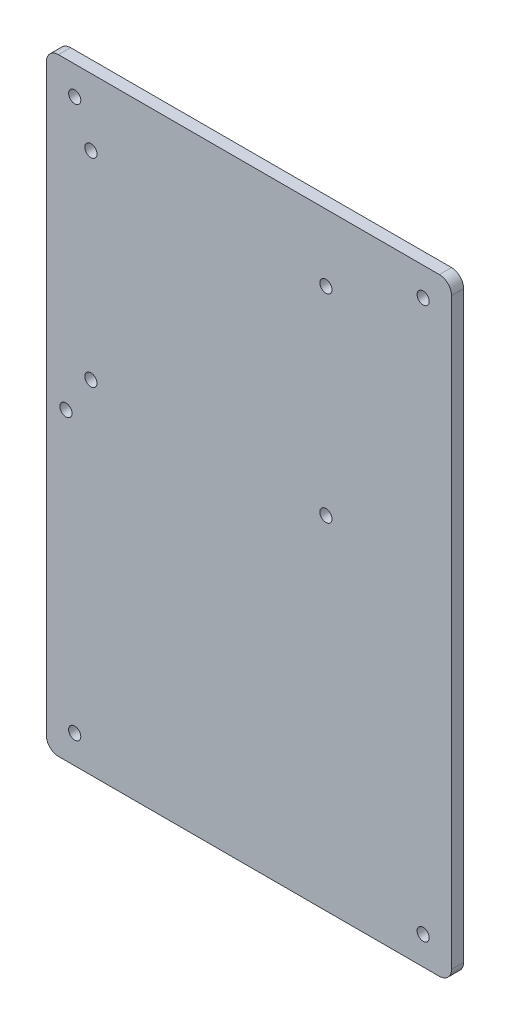
SolidWorks part; units mm, degrees
ref_plane "前视基准面" through (0, 0, 0) normal (0, 0, 1) x (1, 0, 0)
ref_plane "上视基准面" through (0, 0, 0) normal (0, 1, 0) x (1, 0, 0)
ref_plane "右视基准面" through (0, 0, 0) normal (1, 0, 0) x (0, 0, -1)
ref_plane "基准面4" through (0, 0, 43) normal (0, 0, 1) x (1, 0, 0)
sketch "草图1" plane through (0, 0, 43) normal (0, 0, 1) x (1, 0, 0)
  line L0 (-102, -62) -> (-8, -62)
  line L1 (-5, -59) -> (-5, 85)
  line L2 (-8, 88) -> (-102, 88)
  line L3 (-105, 85) -> (-105, -59)
  circle A0 centre (-94, 71.5) radius 1.5
  circle A1 centre (-94, 22.5) radius 1.5
  circle A2 centre (-36, 22.5) radius 1.5
  circle A3 centre (-36, 71.5) radius 1.5
  circle A4 centre (-100.157, 13) radius 1.5
  circle A5 centre (-12, 81) radius 1.5
  circle A6 centre (-98, -55) radius 1.5
  circle A7 centre (-98, 81) radius 1.5
  circle A8 centre (-12, -55) radius 1.5
  arc A9 (-8, -62) -> (-5, -59) centre (-8, -59) ccw
  arc A10 (-5, 85) -> (-8, 88) centre (-8, 85) ccw
  arc A11 (-102, 88) -> (-105, 85) centre (-102, 85) ccw
  arc A12 (-105, -59) -> (-102, -62) centre (-102, -59) ccw
extrude "凸台-拉伸1" add sketch "草图1" against normal blind 3
